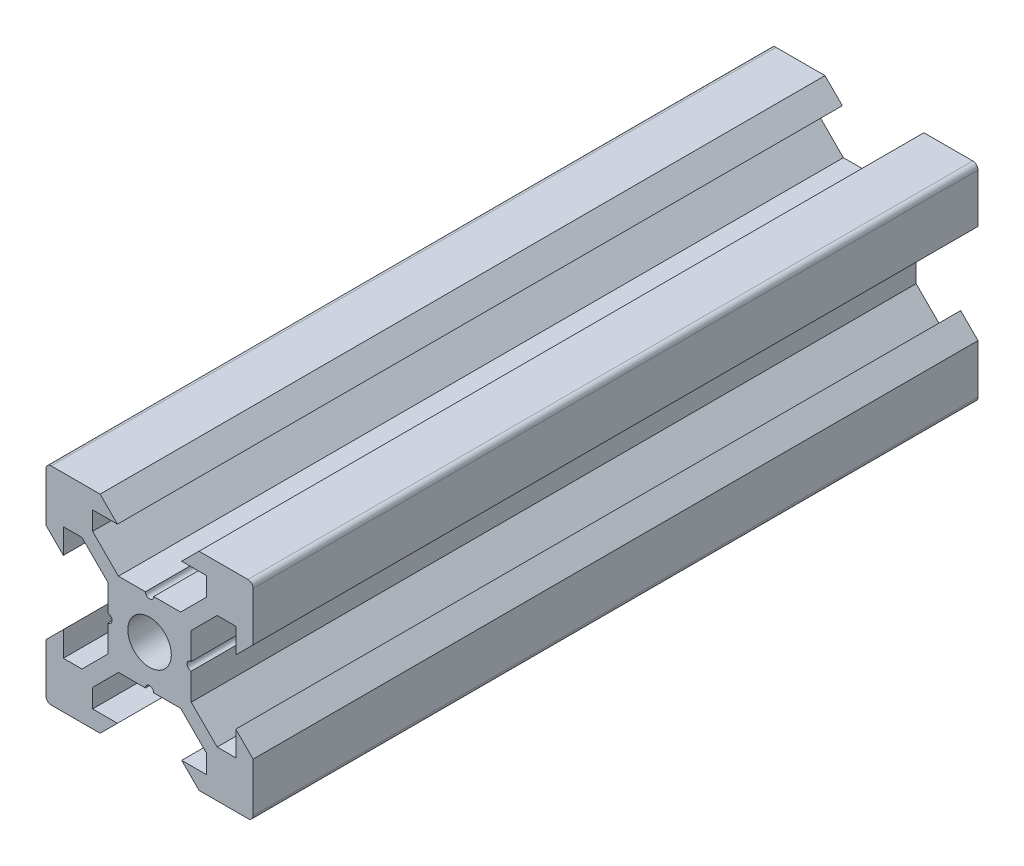
SolidWorks part; units mm, degrees
ref_plane "Front Plane" through (0, 0, 0) normal (0, 0, 1) x (1, 0, 0)
ref_plane "Top Plane" through (0, 0, 0) normal (0, 1, 0) x (1, 0, 0)
ref_plane "Right Plane" through (0, 0, 0) normal (1, 0, 0) x (0, 0, -1)
sketch "Sketch1" plane through (0, 0, 0) normal (0, 0, 1) x (1, 0, 0)
  line L0 (0, 11.7715) -> (0, -11.0375) construction
  line L1 (-10, 10) -> (10, 10) construction
  line L2 (-10, 10) -> (-10, -10) construction
  line L3 (-10, -10) -> (10, -10) construction
  line L4 (10, 10) -> (10, -10) construction
  line L5 (-10, 10) -> (10, -10) construction
  line L6 (-10, -10) -> (10, 10) construction
  line L7 (-5.5, 5.5) -> (5.5, 5.5) construction
  line L8 (-5.5, 5.5) -> (-5.5, -5.5) construction
  line L9 (-5.5, -5.5) -> (5.5, -5.5) construction
  line L10 (5.5, 5.5) -> (5.5, -5.5) construction
  line L11 (-5.5, 5.5) -> (5.5, -5.5) construction
  line L12 (-5.5, -5.5) -> (5.5, 5.5) construction
  line L13 (-10, 10) -> (-4.775, 10)
  line L14 (-4.775, 10) -> (-3.1, 8.325)
  line L15 (-3.1, 8.325) -> (-5.5, 8.325)
  line L16 (-5.5, 8.325) -> (-5.5, 6.525)
  line L17 (-5.5, 6.525) -> (-3, 4.025)
  line L18 (-3, 4.025) -> (3, 4.025)
  line L19 (-2.8044, 0) -> (3.0922, 0) construction
  line L20 (5.5, 6.525) -> (3, 4.025)
  line L21 (5.5, 8.325) -> (5.5, 6.525)
  line L22 (3.1, 8.325) -> (5.5, 8.325)
  line L23 (4.775, 10) -> (3.1, 8.325)
  line L24 (10, 10) -> (4.775, 10)
  line L25 (10, -10) -> (4.775, -10)
  line L26 (4.775, -10) -> (3.1, -8.325)
  line L27 (3.1, -8.325) -> (5.5, -8.325)
  line L28 (5.5, -8.325) -> (5.5, -6.525)
  line L29 (5.5, -6.525) -> (3, -4.025)
  line L30 (-3.1, -8.325) -> (-5.5, -8.325)
  line L31 (-3, -4.025) -> (3, -4.025)
  line L32 (-5.5, -6.525) -> (-3, -4.025)
  line L33 (-5.5, -8.325) -> (-5.5, -6.525)
  line L34 (-4.775, -10) -> (-3.1, -8.325)
  line L35 (-10, -10) -> (-4.775, -10)
  line L36 (-4.025, 3) -> (-4.025, -3)
  line L37 (-6.525, 5.5) -> (-4.025, 3)
  line L38 (-8.325, 5.5) -> (-6.525, 5.5)
  line L39 (-8.325, 3.1) -> (-8.325, 5.5)
  line L40 (-10, 4.775) -> (-8.325, 3.1)
  line L41 (-10, 10) -> (-10, 4.775)
  line L42 (-10, -10) -> (-10, -4.775)
  line L43 (-10, -4.775) -> (-8.325, -3.1)
  line L44 (-8.325, -3.1) -> (-8.325, -5.5)
  line L45 (-8.325, -5.5) -> (-6.525, -5.5)
  line L46 (-6.525, -5.5) -> (-4.025, -3)
  line L47 (10, -10) -> (10, -4.775)
  line L48 (10, -4.775) -> (8.325, -3.1)
  line L49 (8.325, -3.1) -> (8.325, -5.5)
  line L50 (8.325, -5.5) -> (6.525, -5.5)
  line L51 (6.525, -5.5) -> (4.025, -3)
  line L52 (4.025, 3) -> (4.025, -3)
  line L53 (6.525, 5.5) -> (4.025, 3)
  line L54 (8.325, 5.5) -> (6.525, 5.5)
  line L55 (8.325, 3.1) -> (8.325, 5.5)
  line L56 (10, 4.775) -> (8.325, 3.1)
  line L57 (10, 10) -> (10, 4.775)
  circle A0 centre (0, 0) radius 2.1
  point P0 (0, 0)
  point P6 (0, 0)
  point P23 (0, 4.025)
  dimension "D3" = 4.2
  dimension "D1" = 20
  dimension "D2" = 20
  dimension "D4" = 45
  dimension "D5" = 45
  dimension "D6" = 9.55
  dimension "D7" = 6.2
  dimension "D8" = 11
  dimension "D9" = 1.675
  dimension "D10" = 4.3
  dimension "D11" = 9.55
  dimension "D12" = 6.2
  dimension "D13" = 1.675
  dimension "D14" = 4.3
  dimension "D15" = 1.8
  dimension "D16" = 1.8
  dimension "D17" = 45
extrude "Boss-Extrude1" add sketch "Sketch1" along normal blind 70
fillet "Fillet1" radius 0.5 4 edges at (-10, -10, 35) (10, -10, 35) (10, 10, 35) (-10, 10, 35)
sketch "Sketch2" plane through (0, 0, 70) normal (0, 0, 1) x (1, 0, 0)
  line L0 (-0.8203, 0) -> (1.3478, 0) construction
  line L1 (0, 1.2196) -> (0, -1.1398) construction
  line L44 (-10, -4.775) -> (-10, -9.5)
  line L45 (-9.5, -10) -> (-4.775, -10)
  line L46 (-4.775, -10) -> (-3.1, -8.325)
  line L47 (-3.1, -8.325) -> (-5.5, -8.325)
  line L48 (-5.5, -8.325) -> (-5.5, -6.525)
  line L49 (-5.5, -6.525) -> (-3, -4.025)
  line L50 (-3, -4.025) -> (3, -4.025)
  line L51 (3, -4.025) -> (5.5, -6.525)
  line L52 (5.5, -6.525) -> (5.5, -8.325)
  line L53 (5.5, -8.325) -> (3.1, -8.325)
  line L54 (3.1, -8.325) -> (4.775, -10)
  line L55 (4.775, -10) -> (9.5, -10)
  line L56 (10, -9.5) -> (10, -4.775)
  line L57 (10, -4.775) -> (8.325, -3.1)
  line L58 (8.325, -3.1) -> (8.325, -5.5)
  line L59 (8.325, -5.5) -> (6.525, -5.5)
  line L60 (6.525, -5.5) -> (4.025, -3)
  line L61 (4.025, -3) -> (4.025, 3)
  line L62 (4.025, 3) -> (6.525, 5.5)
  line L63 (6.525, 5.5) -> (8.325, 5.5)
  line L64 (8.325, 5.5) -> (8.325, 3.1)
  line L65 (8.325, 3.1) -> (10, 4.775)
  line L66 (10, 4.775) -> (10, 9.5)
  line L67 (9.5, 10) -> (4.775, 10)
  line L68 (4.775, 10) -> (3.1, 8.325)
  line L69 (3.1, 8.325) -> (5.5, 8.325)
  line L70 (5.5, 8.325) -> (5.5, 6.525)
  line L71 (5.5, 6.525) -> (3, 4.025)
  line L72 (3, 4.025) -> (-3, 4.025)
  line L73 (-3, 4.025) -> (-5.5, 6.525)
  line L74 (-5.5, 6.525) -> (-5.5, 8.325)
  line L75 (-5.5, 8.325) -> (-3.1, 8.325)
  line L76 (-3.1, 8.325) -> (-4.775, 10)
  line L77 (-4.775, 10) -> (-9.5, 10)
  line L78 (-10, 9.5) -> (-10, 4.775)
  line L79 (-10, 4.775) -> (-8.325, 3.1)
  line L80 (-8.325, 3.1) -> (-8.325, 5.5)
  line L81 (-8.325, 5.5) -> (-6.525, 5.5)
  line L82 (-6.525, 5.5) -> (-4.025, 3)
  line L83 (-4.025, 3) -> (-4.025, -3)
  line L84 (-4.025, -3) -> (-6.525, -5.5)
  line L85 (-6.525, -5.5) -> (-8.325, -5.5)
  line L86 (-8.325, -5.5) -> (-8.325, -3.1)
  line L87 (-8.325, -3.1) -> (-10, -4.775)
  line L88 (-10, -4.775) -> (-10, -9.5)
  line L89 (-9.5, -10) -> (-4.775, -10)
  line L90 (-4.775, -10) -> (-3.1, -8.325)
  line L91 (-3.1, -8.325) -> (-5.5, -8.325)
  line L92 (-5.5, -8.325) -> (-5.5, -6.525)
  line L93 (-5.5, -6.525) -> (-3, -4.025)
  line L94 (-3, -4.025) -> (3, -4.025)
  line L95 (3, -4.025) -> (5.5, -6.525)
  line L96 (5.5, -6.525) -> (5.5, -8.325)
  line L97 (5.5, -8.325) -> (3.1, -8.325)
  line L98 (3.1, -8.325) -> (4.775, -10)
  line L99 (4.775, -10) -> (9.5, -10)
  line L100 (10, -9.5) -> (10, -4.775)
  line L101 (10, -4.775) -> (8.325, -3.1)
  line L102 (8.325, -3.1) -> (8.325, -5.5)
  line L103 (8.325, -5.5) -> (6.525, -5.5)
  line L104 (6.525, -5.5) -> (4.025, -3)
  line L105 (4.025, -3) -> (4.025, 3)
  line L106 (4.025, 3) -> (6.525, 5.5)
  line L107 (6.525, 5.5) -> (8.325, 5.5)
  line L108 (8.325, 5.5) -> (8.325, 3.1)
  line L109 (8.325, 3.1) -> (10, 4.775)
  line L110 (10, 4.775) -> (10, 9.5)
  line L111 (9.5, 10) -> (4.775, 10)
  line L112 (4.775, 10) -> (3.1, 8.325)
  line L113 (3.1, 8.325) -> (5.5, 8.325)
  line L114 (5.5, 8.325) -> (5.5, 6.525)
  line L115 (5.5, 6.525) -> (3, 4.025)
  line L116 (3, 4.025) -> (-3, 4.025)
  line L117 (-3, 4.025) -> (-5.5, 6.525)
  line L118 (-5.5, 6.525) -> (-5.5, 8.325)
  line L119 (-5.5, 8.325) -> (-3.1, 8.325)
  line L120 (-3.1, 8.325) -> (-4.775, 10)
  line L121 (-4.775, 10) -> (-9.5, 10)
  line L122 (-10, 9.5) -> (-10, 4.775)
  line L123 (-10, 4.775) -> (-8.325, 3.1)
  line L124 (-8.325, 3.1) -> (-8.325, 5.5)
  line L125 (-8.325, 5.5) -> (-6.525, 5.5)
  line L126 (-6.525, 5.5) -> (-4.025, 3)
  line L127 (-4.025, 3) -> (-4.025, -3)
  line L128 (-4.025, -3) -> (-6.525, -5.5)
  line L129 (-6.525, -5.5) -> (-8.325, -5.5)
  line L130 (-8.325, -5.5) -> (-8.325, -3.1)
  line L131 (-8.325, -3.1) -> (-10, -4.775)
  circle A0 centre (-4.025, 0) radius 0.4
  circle A1 centre (4.025, 0) radius 0.4
  circle A2 centre (0, 4.025) radius 0.4
  circle A3 centre (0, -4.025) radius 0.4
  arc A4 (-10, -9.5) -> (-9.5, -10) centre (-9.5, -9.5) ccw
  arc A5 (9.5, -10) -> (10, -9.5) centre (9.5, -9.5) ccw
  arc A6 (10, 9.5) -> (9.5, 10) centre (9.5, 9.5) ccw
  arc A7 (-9.5, 10) -> (-10, 9.5) centre (-9.5, 9.5) ccw
  arc A8 (-10, -9.5) -> (-9.5, -10) centre (-9.5, -9.5) ccw
  arc A9 (9.5, -10) -> (10, -9.5) centre (9.5, -9.5) ccw
  arc A10 (10, 9.5) -> (9.5, 10) centre (9.5, 9.5) ccw
  arc A11 (-9.5, 10) -> (-10, 9.5) centre (-9.5, 9.5) ccw
  dimension "D2" = 0.8
  dimension "D3" = 0.8
  dimension "D1" = 0
extrude "Cut-Extrude1" cut sketch "Sketch2" against normal through all contours L127 A0 | L116 A2 | A1 L105 | A3 L94
